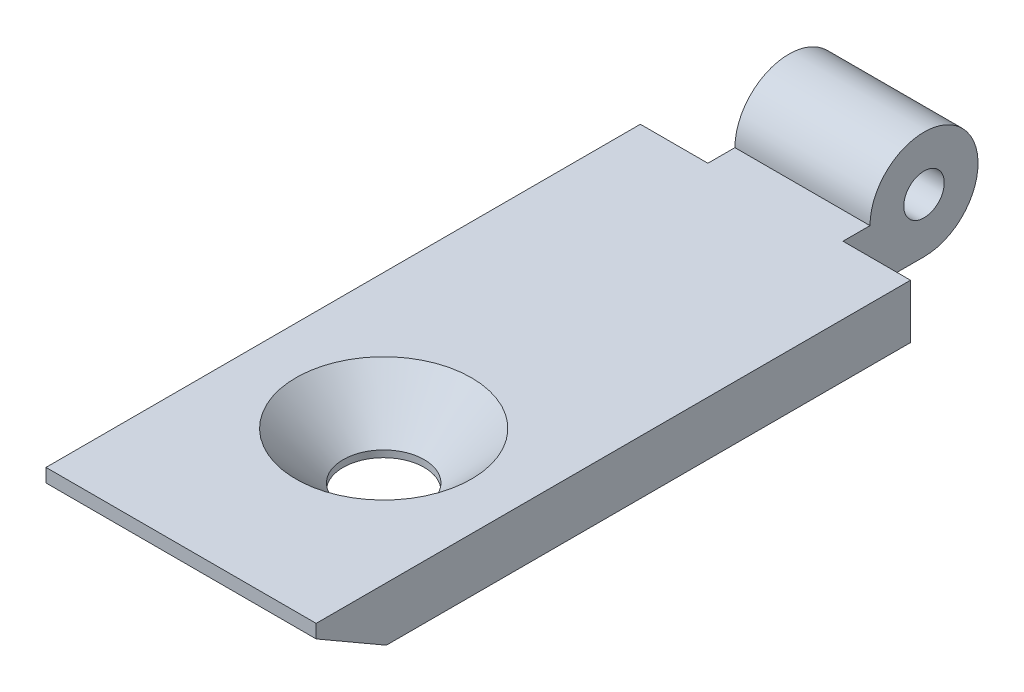
SolidWorks part; units mm, degrees
material "1060 合金"
ref_plane "前视基准面" through (0, 0, 0) normal (0, 0, 1) x (1, 0, 0)
ref_plane "上视基准面" through (0, 0, 0) normal (0, 1, 0) x (1, 0, 0)
ref_plane "右视基准面" through (0, 0, 0) normal (1, 0, 0) x (0, 0, -1)
sketch "草图1" plane through (0, 0, 0) normal (1, 0, 0) x (0, 0, -1)
  line L0 (0, -4) -> (-44.8038, -4)
  line L1 (-44.8038, -4) -> (-50, -1)
  line L2 (-50, -1) -> (-50, 0)
  line L3 (-50, 0) -> (-4, 0)
  arc A0 (0, -4) -> (-4, 0) centre (0, 0) ccw
  circle A1 centre (0, 0) radius 1.5
  dimension "D1" = 4
  dimension "D2" = 3
  dimension "D3" = 50
  dimension "D4" = 1
  dimension "D5" = 30
extrude "凸台-拉伸1" add sketch "草图1" along normal mid plane 20
sketch "草图3" plane through (0, 0, 0) normal (0, 1, 0) x (1, 0, 0)
  line L0 (0, 4) -> (0, -50) construction
  line L1 (-10, 4) -> (-5, 4)
  line L2 (-10, 4) -> (-10, -6)
  line L3 (-10, -6) -> (-5, -6)
  line L4 (-5, 4) -> (-5, -6)
  line L9 (10, 4) -> (-10, 4) construction
  line L10 (10, -50) -> (-10, -50) construction
  line L12 (5, 4) -> (5, -6)
  line L13 (10, -6) -> (5, -6)
  line L14 (10, 4) -> (10, -6)
  line L15 (10, 4) -> (5, 4)
  circle A0 centre (0, -35) radius 3
  dimension "D1" = 6
  dimension "D2" = 35
  dimension "D3" = 10
  dimension "D4" = 5
extrude "切除-拉伸1" cut sketch "草图3" against normal through all both and the other way through all
chamfer "倒角1" distance 3.5 angle 45 1 edges at (0, 0, 32)
